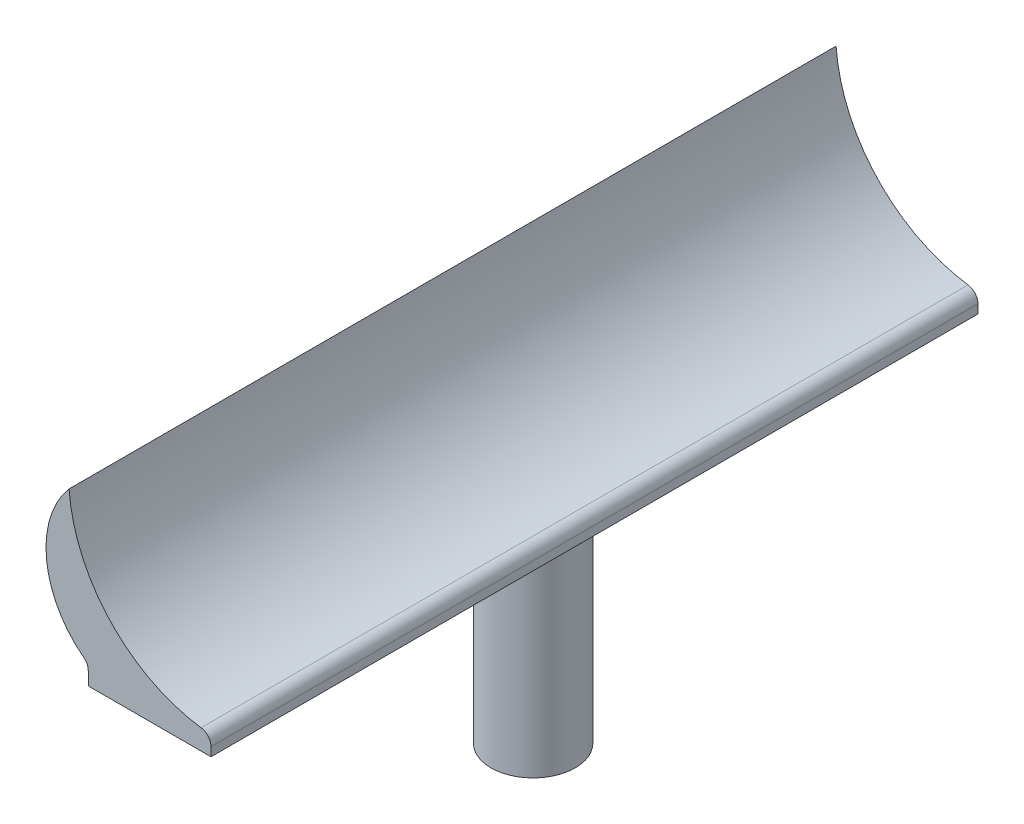
SolidWorks part; units mm, degrees
ref_plane "Front Plane" through (0, 0, 0) normal (0, 0, 1) x (1, 0, 0)
ref_plane "Top Plane" through (0, 0, 0) normal (0, 1, 0) x (1, 0, 0)
ref_plane "Right Plane" through (0, 0, 0) normal (1, 0, 0) x (0, 0, -1)
sketch "Sketch1" plane through (0, 0, 0) normal (0, 1, 0) x (1, 0, 0)
  circle A0 centre (0, 0) radius 11
  dimension "D1" = 22
extrude "Boss-Extrude1" add sketch "Sketch1" along normal blind 55
sketch "Sketch2" plane through (0, 0, 0) normal (0, 0, 1) x (1, 0, 0)
  line L0 (-16, 55) -> (16, 55)
  line L1 (16, 55) -> (16, 60)
  line L2 (0, 0) -> (0, 42.7081) construction
  line L3 (-16, 55) -> (-16, 60)
  line L4 (11, 55) -> (-11, 55) construction
  line L5 (-11, 55) -> (-11, 0) construction
  arc A0 (-16, 60) -> (-21, 97) centre (-2.0215, 80.7268) cw
  arc A1 (-21, 97) -> (16, 60) centre (18.8951, 99.8951) ccw
  dimension "D5" = 25
  dimension "D6" = 40
  dimension "D1" = 32
  dimension "D2" = 5
  dimension "D3" = 42
  dimension "D4" = 10
extrude "Boss-Extrude2" add sketch "Sketch2" along normal mid plane 200
fillet "Fillet1" radius 3 2 edges at (-16, 60, 0) (16, 60, 0)
